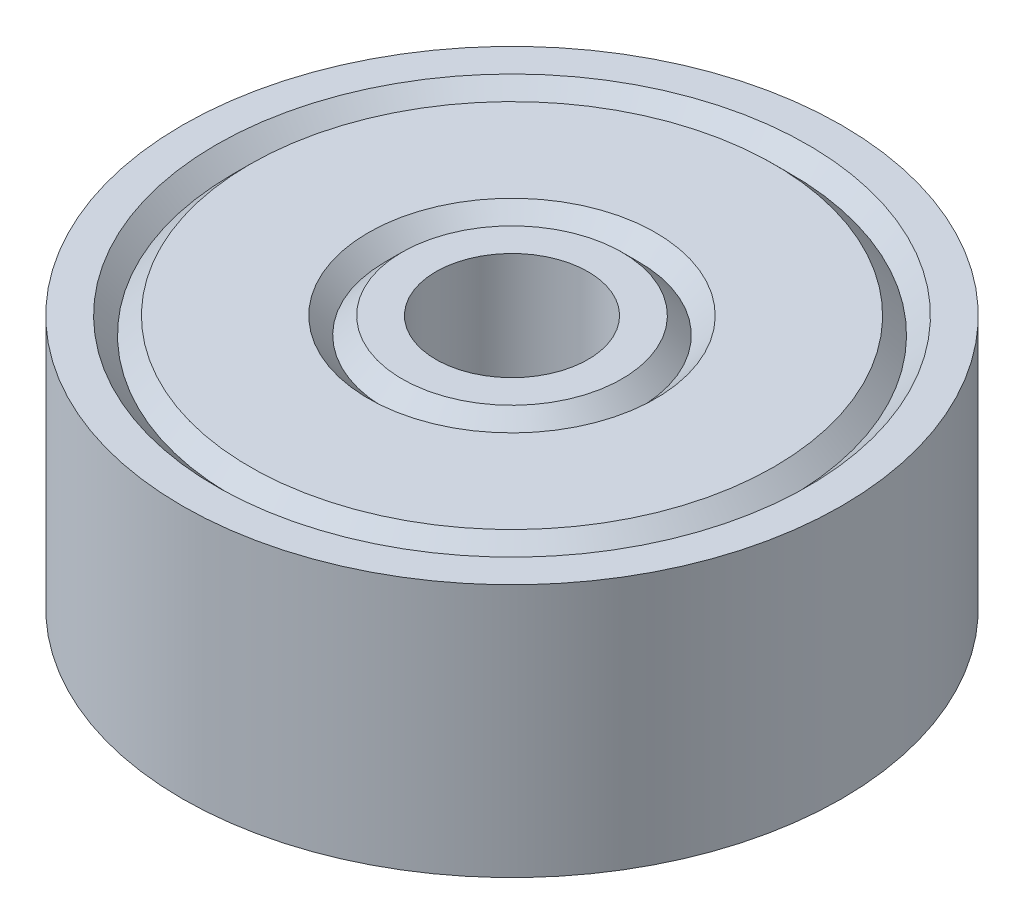
SolidWorks part; units mm, degrees
ref_plane "Front Plane" through (0, 0, 0) normal (0, 0, 1) x (1, 0, 0)
ref_plane "Top Plane" through (0, 0, 0) normal (0, 1, 0) x (1, 0, 0)
ref_plane "Right Plane" through (0, 0, 0) normal (1, 0, 0) x (0, 0, -1)
sketch "Sketch1" plane through (0, 0, 0) normal (0, 0, 1) x (1, 0, 0)
  line L0 (0, 2.5) -> (0, -2.5) construction
  line L1 (-1.5, 2.5) -> (-2.1667, 2.5)
  line L2 (-1.5, 2.5) -> (-1.5, -2.5)
  line L3 (-1.5, -2.5) -> (-2.1667, -2.5)
  line L4 (-6.5, 2.5) -> (-6.5, -2.5)
  line L5 (-5.8333, 2.5) -> (-5.5, 2.1667)
  line L6 (-5.5, 2.1667) -> (-5.1667, 2.5)
  line L7 (-2.8333, 2.5) -> (-2.5, 2.1667)
  line L8 (-2.5, 2.1667) -> (-2.1667, 2.5)
  line L9 (-5.8333, -2.5) -> (-5.5, -2.1667)
  line L10 (-5.5, -2.1667) -> (-5.1667, -2.5)
  line L11 (-2.8333, -2.5) -> (-2.5, -2.1667)
  line L12 (-2.5, -2.1667) -> (-2.1667, -2.5)
  line L13 (-2.8333, -2.5) -> (-5.1667, -2.5)
  line L14 (-5.8333, -2.5) -> (-6.5, -2.5)
  line L15 (-5.8333, 2.5) -> (-6.5, 2.5)
  line L16 (-2.8333, 2.5) -> (-5.1667, 2.5)
  line L17 (-5.5, 2.1667) -> (-2.5, 2.1667) construction
  line L18 (-5.5, 2.1667) -> (-5.5, -2.1667) construction
  line L19 (-2.5, -2.1667) -> (-5.5, -2.1667) construction
  line L20 (-2.5, 2.1667) -> (-2.5, -2.1667) construction
  line L21 (-5.5, 0) -> (-4.5, 0) construction
  line L22 (-2.1667, 2.5) -> (-2.8333, 2.5) construction
  line L23 (-4.5, 0) -> (-3.5, 0) construction
  line L24 (-5.5, 0) -> (-6.5, 0) construction
  line L25 (-3.5, 0) -> (-2.5, 0) construction
  line L26 (-2.5, 0) -> (-1.5, 0) construction
  dimension "D1" = 5
  dimension "D2" = 3
  dimension "D3" = 13
revolve "Revolve1" add sketch "Sketch1" angle 360 about L0
